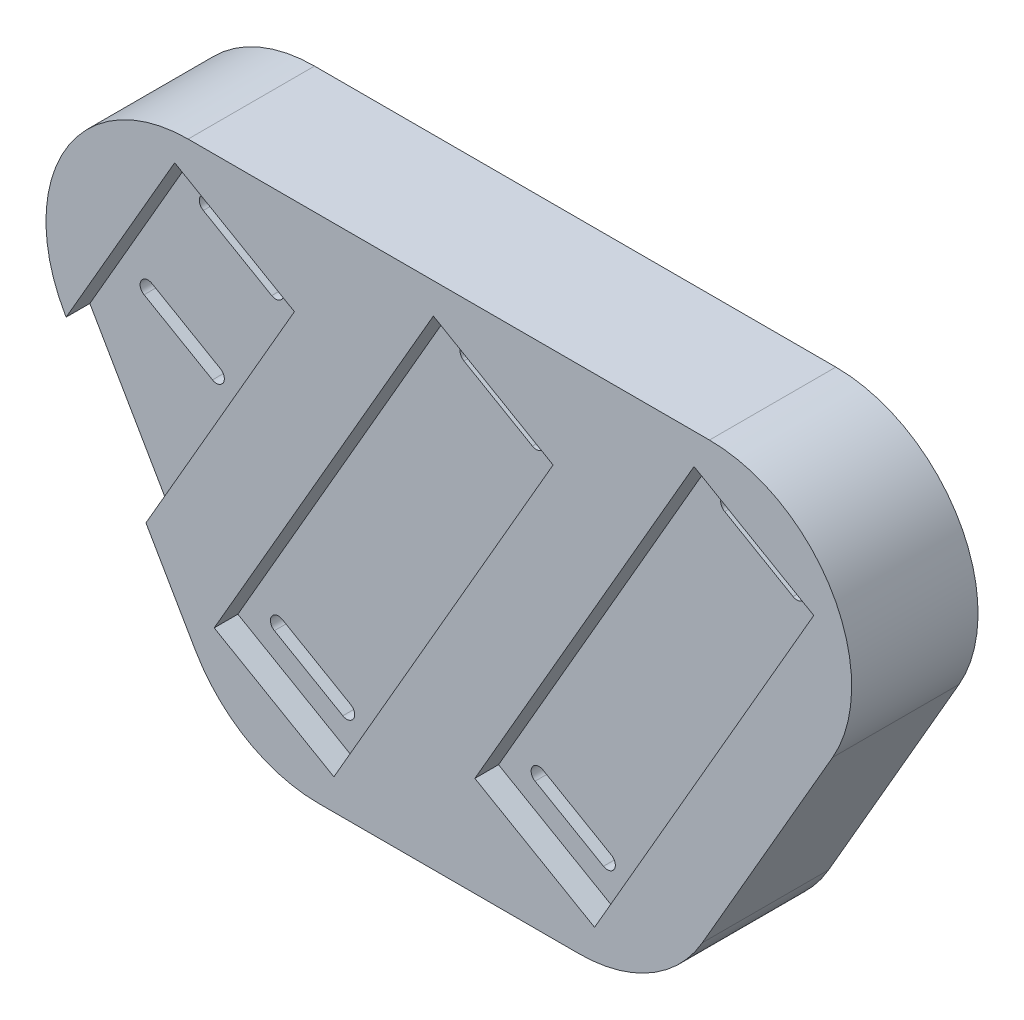
SolidWorks part; units mm, degrees
ref_plane "Front Plane" through (0, 0, 0) normal (0, 0, 1) x (1, 0, 0)
ref_plane "Top Plane" through (0, 0, 0) normal (0, 1, 0) x (1, 0, 0)
ref_plane "Right Plane" through (0, 0, 0) normal (1, 0, 0) x (0, 0, -1)
sketch "Sketch1" plane through (0, 0, 0) normal (0, 0, 1) x (1, 0, 0)
  line L0 (0, 0) -> (-16.5, 0) construction
  line L1 (-8.25, -14.2894) -> (-24.75, -14.2894) construction
  line L2 (0, 0) -> (-8.25, -14.2894) construction
  line L3 (-8.25, -14.2894) -> (-16.5, 0) construction
  line L4 (-16.5, 0) -> (-24.75, -14.2894) construction
  line L5 (-24.75, -14.2894) -> (-33, 0) construction
  line L6 (-33, 0) -> (-16.5, 0) construction
  line L7 (8.9827, 0.5584) -> (-3.9199, -21.7894) construction
  line L8 (-3.9199, -21.7894) -> (-29.0801, -21.7894) construction
  line L9 (-29.0801, -21.7894) -> (-41.9827, 0.5584) construction
  line L10 (-37.9749, 7.5) -> (4.9749, 7.5) construction
  line L11 (7.7942, -4.5) -> (-0.4558, -18.7894)
  line L12 (-8.25, -23.2894) -> (-24.75, -23.2894)
  line L13 (-32.5442, -18.7894) -> (-40.7942, -4.5)
  line L14 (-33, 9) -> (0, 9)
  line L15 (2.5314, -10.6155) -> (3.8304, -11.3655) construction
  line L16 (-16.5, -21.7894) -> (-16.5, -23.2894) construction
  line L17 (-35.5314, -10.6155) -> (-36.8304, -11.3655) construction
  line L18 (-16.5, 7.5) -> (-16.5, 9) construction
  circle A0 centre (-24.75, -14.2894) radius 7.5
  circle A1 centre (-16.5, 0) radius 7.5
  circle A2 centre (0, 0) radius 7.5
  circle A3 centre (0, 0) radius 7.5
  circle A4 centre (-8.25, -14.2894) radius 7.5
  circle A5 centre (-33, 0) radius 7.5
  arc A6 (7.7942, -4.5) -> (0, 9) centre (0, 0) ccw
  arc A7 (-33, 9) -> (-40.7942, -4.5) centre (-33, 0) ccw
  arc A8 (-0.4558, -18.7894) -> (-8.25, -23.2894) centre (-8.25, -14.2894) cw
  arc A9 (-24.75, -23.2894) -> (-32.5442, -18.7894) centre (-24.75, -14.2894) cw
  point P28 (2.5314, -10.6155)
  point P30 (-16.5, -21.7894)
  point P32 (-35.5314, -10.6155)
  point P35 (-16.5, 9)
  dimension "D2" = 15
  dimension "D3" = 16.5
  dimension "D4" = 1.5
  dimension "D5" = 1.5
  dimension "D1" = 0.25
extrude "Boss-Extrude1" add sketch "Sketch1" along normal blind 5
sketch "Sketch2" plane through (0, 0, 5) normal (0, 0, 1) x (1, 0, 0)
  line L0 (-0.4558, -18.7894) -> (7.7942, -4.5) construction
  line L1 (0, 9) -> (-33, 9) construction
  line L2 (-40.7942, -4.5) -> (-32.5442, -18.7894) construction
  line L3 (-24.75, -23.2894) -> (-8.25, -23.2894) construction
  line L4 (-0.4558, -18.7894) -> (7.7942, -4.5)
  line L5 (0, 9) -> (-33, 9)
  line L6 (-40.7942, -4.5) -> (-32.5442, -18.7894)
  line L7 (-24.75, -23.2894) -> (-8.25, -23.2894)
  line L8 (4.0401, 1.9976) -> (-0.2901, 4.4976) construction
  line L9 (3.7901, 1.5646) -> (-0.5401, 4.0646)
  line L10 (4.2901, 2.4306) -> (-0.0401, 4.9306)
  line L11 (-7.9599, -18.787) -> (-12.2901, -16.287) construction
  line L12 (-8.2099, -19.22) -> (-12.5401, -16.72)
  line L13 (-7.7099, -18.354) -> (-12.0401, -15.854)
  line L14 (1.875, 3.2476) -> (-10.125, -17.537) construction
  line L15 (-26.625, -17.537) -> (-24.75, -14.2894) construction
  line L16 (0, 0) -> (1.875, 3.2476) construction
  line L17 (1.875, 3.2476) -> (3.75, 6.4952) construction
  line L18 (-10.125, -17.537) -> (-12, -20.7846) construction
  line L19 (-10.125, -17.537) -> (-8.25, -14.2894) construction
  line L20 (-14.625, 3.2476) -> (-12.75, 6.4952) construction
  line L21 (-14.625, 3.2476) -> (-26.625, -17.537) construction
  line L22 (-16.5, 0) -> (-14.625, 3.2476) construction
  line L23 (-26.625, -17.537) -> (-28.5, -20.7846) construction
  line L24 (-12.4599, 1.9976) -> (-16.7901, 4.4976) construction
  line L25 (-12.7099, 1.5646) -> (-17.0401, 4.0646)
  line L26 (-12.2099, 2.4306) -> (-16.5401, 4.9306)
  line L27 (-24.4599, -18.787) -> (-28.7901, -16.287) construction
  line L28 (-24.7099, -19.22) -> (-29.0401, -16.72)
  line L29 (-24.2099, -18.354) -> (-28.5401, -15.854)
  line L30 (-28.9599, 1.9976) -> (-33.2901, 4.4976) construction
  line L31 (-29.2099, 1.5646) -> (-33.5401, 4.0646)
  line L32 (-28.7099, 2.4306) -> (-33.0401, 4.9306)
  line L33 (-32.7099, -4.4976) -> (-37.0401, -1.9976) construction
  line L34 (-32.9599, -4.9306) -> (-37.2901, -2.4306)
  line L35 (-32.4599, -4.0646) -> (-36.7901, -1.5646)
  line L36 (-31.125, 3.2476) -> (-34.875, -3.2476) construction
  line L37 (-31.125, 3.2476) -> (-29.25, 6.4952) construction
  line L38 (-34.875, -3.2476) -> (-36.75, -6.4952) construction
  line L39 (-31.125, 3.2476) -> (-33, 0) construction
  arc A0 (-8.25, -23.2894) -> (-0.4558, -18.7894) centre (-8.25, -14.2894) ccw construction
  arc A1 (7.7942, -4.5) -> (0, 9) centre (0, 0) ccw construction
  arc A2 (-33, 9) -> (-40.7942, -4.5) centre (-33, 0) ccw construction
  arc A3 (-32.5442, -18.7894) -> (-24.75, -23.2894) centre (-24.75, -14.2894) ccw construction
  arc A4 (-8.25, -23.2894) -> (-0.4558, -18.7894) centre (-8.25, -14.2894) ccw
  arc A5 (7.7942, -4.5) -> (0, 9) centre (0, 0) ccw
  arc A6 (-33, 9) -> (-40.7942, -4.5) centre (-33, 0) ccw
  arc A7 (-32.5442, -18.7894) -> (-24.75, -23.2894) centre (-24.75, -14.2894) ccw
  circle A8 centre (-33, 0) radius 7.5 construction
  circle A9 centre (-24.75, -14.2894) radius 7.5 construction
  circle A10 centre (-16.5, 0) radius 7.5 construction
  circle A11 centre (-8.25, -14.2894) radius 7.5 construction
  circle A12 centre (0, 0) radius 7.5 construction
  circle A13 centre (-33, 0) radius 7.5
  circle A14 centre (-24.75, -14.2894) radius 7.5
  circle A15 centre (-16.5, 0) radius 7.5
  circle A16 centre (-8.25, -14.2894) radius 7.5
  circle A17 centre (0, 0) radius 7.5
  arc A18 (3.7901, 1.5646) -> (4.2901, 2.4306) centre (4.0401, 1.9976) ccw
  arc A19 (-0.0401, 4.9306) -> (-0.5401, 4.0646) centre (-0.2901, 4.4976) ccw
  arc A20 (-8.2099, -19.22) -> (-7.7099, -18.354) centre (-7.9599, -18.787) ccw
  arc A21 (-12.0401, -15.854) -> (-12.5401, -16.72) centre (-12.2901, -16.287) ccw
  arc A22 (-12.7099, 1.5646) -> (-12.2099, 2.4306) centre (-12.4599, 1.9976) ccw
  arc A23 (-16.5401, 4.9306) -> (-17.0401, 4.0646) centre (-16.7901, 4.4976) ccw
  arc A24 (-24.7099, -19.22) -> (-24.2099, -18.354) centre (-24.4599, -18.787) ccw
  arc A25 (-28.5401, -15.854) -> (-29.0401, -16.72) centre (-28.7901, -16.287) ccw
  arc A26 (-29.2099, 1.5646) -> (-28.7099, 2.4306) centre (-28.9599, 1.9976) ccw
  arc A27 (-33.0401, 4.9306) -> (-33.5401, 4.0646) centre (-33.2901, 4.4976) ccw
  arc A28 (-32.9599, -4.9306) -> (-32.4599, -4.0646) centre (-32.7099, -4.4976) ccw
  arc A29 (-36.7901, -1.5646) -> (-37.2901, -2.4306) centre (-37.0401, -1.9976) ccw
  point P8 (-31.125, 3.2476)
  point P25 (1.875, 3.2476)
  point P32 (-10.125, -17.537)
  point P45 (-14.625, 3.2476)
  point P52 (-26.625, -17.537)
  point P64 (-34.875, -3.2476)
  circle M1 centre (-8.25, -14.2894) radius 7.5
  circle M2 centre (0, 0) radius 7.5
  arc M3 (7.7942, -4.5) -> (0, 9) centre (0, 0) ccw
  line M4 (0, 9) -> (-33, 9)
  arc M5 (-33, 9) -> (-40.7942, -4.5) centre (-33, 0) ccw
  line M6 (-40.7942, -4.5) -> (-32.5442, -18.7894)
  arc M7 (-32.5442, -18.7894) -> (-24.75, -23.2894) centre (-24.75, -14.2894) ccw
  line M8 (-24.75, -23.2894) -> (-8.25, -23.2894)
  arc M9 (-8.25, -23.2894) -> (-0.4558, -18.7894) centre (-8.25, -14.2894) ccw
  line M10 (-0.4558, -18.7894) -> (7.7942, -4.5)
  circle M11 centre (-16.5, 0) radius 7.5
  circle M12 centre (-24.75, -14.2894) radius 7.5
  circle M13 centre (-33, 0) radius 7.5
  dimension "D1" = 1
  dimension "D2" = 5
extrude "Boss-Extrude2" add sketch "Sketch2" along normal blind 1.5 contours A21 L13 A20 L12 M1 | M10 M3 M4 M5 M6 M7 M8 M9 M2 M11 M13 M12 M1 | A19 L10 A18 L9 M2 | A23 L26 A22 L25 M11 | A25 L29 A24 L28 M12 | A29 L35 A28 L34 A27 L32 A26 L31 M13
sketch "Sketch3" plane through (0, 0, 6.5) normal (0, 0, 1) x (1, 0, 0)
  line L0 (-40.7942, -4.5) -> (-32.5442, -18.7894) construction
  line L1 (-24.75, -23.2894) -> (-8.25, -23.2894) construction
  line L2 (-0.4558, -18.7894) -> (7.7942, -4.5) construction
  line L3 (0, 9) -> (-33, 9) construction
  line L4 (-40.7942, -4.5) -> (-32.5442, -18.7894)
  line L5 (-24.75, -23.2894) -> (-8.25, -23.2894)
  line L6 (-0.4558, -18.7894) -> (7.7942, -4.5)
  line L7 (0, 9) -> (-33, 9)
  line L8 (6.6014, 2.6839) -> (-7.2736, -21.3483)
  line L9 (6.6014, 2.6839) -> (-0.9764, 7.0589)
  line L10 (-7.2736, -21.3483) -> (-14.8514, -16.9733)
  line L11 (-0.9764, 7.0589) -> (-14.8514, -16.9733)
  line L12 (6.6014, 2.6839) -> (-14.8514, -16.9733) construction
  line L13 (-7.2736, -21.3483) -> (-0.9764, 7.0589) construction
  line L14 (-10.125, -17.537) -> (-12, -20.7846) construction
  line L15 (-10.125, -17.537) -> (-12, -20.7846) construction
  line L16 (-10.375, -17.97) -> (-11.0625, -19.1608) construction
  line L17 (-8.2099, -19.22) -> (-12.5401, -16.72) construction
  line L18 (-12.7231, -16.037) -> (-13.9139, -15.3495) construction
  line L19 (1.875, 3.2476) -> (-10.125, -17.537) construction
  line L20 (1.875, 3.2476) -> (-10.125, -17.537) construction
  line L21 (-26.625, -17.537) -> (-28.5, -20.7846) construction
  line L22 (-14.625, 3.2476) -> (-26.625, -17.537) construction
  line L23 (-26.625, -17.537) -> (-28.5, -20.7846) construction
  line L24 (-14.625, 3.2476) -> (-26.625, -17.537) construction
  line L25 (-9.8986, 2.6839) -> (-23.7736, -21.3483)
  line L26 (-9.8986, 2.6839) -> (-17.4764, 7.0589)
  line L27 (-23.7736, -21.3483) -> (-31.3514, -16.9733)
  line L28 (-17.4764, 7.0589) -> (-31.3514, -16.9733)
  line L29 (-9.8986, 2.6839) -> (-31.3514, -16.9733) construction
  line L30 (-23.7736, -21.3483) -> (-17.4764, 7.0589) construction
  line L31 (-29.2231, -16.037) -> (-30.4139, -15.3495) construction
  line L32 (-26.875, -17.97) -> (-27.5625, -19.1608) construction
  line L33 (-24.7099, -19.22) -> (-29.0401, -16.72) construction
  line L34 (-26.2736, 2.9004) -> (-35.6702, -13.375)
  line L35 (-26.2736, 2.9004) -> (-33.8514, 7.2754)
  line L37 (-33.8514, 7.2754) -> (-40.7221, -4.625)
  line L38 (-26.2736, 2.9004) -> (-39.6518, -6.4788) construction
  line L39 (-35.6702, -13.375) -> (-33.8514, 7.2754) construction
  line L40 (-31.125, 3.2476) -> (-34.875, -3.2476) construction
  line L41 (-30.875, 3.6806) -> (-30.0625, 5.0879) construction
  line L42 (-28.7099, 2.4306) -> (-33.0401, 4.9306) construction
  line L43 (-30.0625, 5.0879) -> (-29.25, 6.4952) construction
  arc A0 (-32.5442, -18.7894) -> (-24.75, -23.2894) centre (-24.75, -14.2894) ccw construction
  arc A1 (-8.25, -23.2894) -> (-0.4558, -18.7894) centre (-8.25, -14.2894) ccw construction
  arc A2 (7.7942, -4.5) -> (0, 9) centre (0, 0) ccw construction
  arc A3 (-33, 9) -> (-40.7942, -4.5) centre (-33, 0) ccw construction
  arc A4 (-32.5442, -18.7894) -> (-24.75, -23.2894) centre (-24.75, -14.2894) ccw
  arc A5 (-8.25, -23.2894) -> (-0.4558, -18.7894) centre (-8.25, -14.2894) ccw
  arc A6 (7.7942, -4.5) -> (0, 9) centre (0, 0) ccw
  arc A7 (-33, 9) -> (-40.7942, -4.5) centre (-33, 0) ccw
  arc A8 (-12.0401, -15.854) -> (-12.5401, -16.72) centre (-12.2901, -16.287) ccw construction
  arc A9 (-28.5401, -15.854) -> (-29.0401, -16.72) centre (-28.7901, -16.287) ccw construction
  point P13 (-4.125, -7.1447)
  point P30 (-11.0625, -19.1608)
  point P33 (-4.125, -7.1447)
  point P35 (-20.625, -7.1447)
  point P49 (-20.625, -7.1447)
  point P50 (-34.7608, -3.0498)
  line M15 (-0.4558, -18.7894) -> (7.7942, -4.5)
  arc M16 (7.7942, -4.5) -> (0, 9) centre (0, 0) ccw
  line M17 (0, 9) -> (-33, 9)
  arc M18 (-33, 9) -> (-40.7942, -4.5) centre (-33, 0) ccw
  line M19 (-40.7942, -4.5) -> (-32.5442, -18.7894)
  arc M20 (-32.5442, -18.7894) -> (-24.75, -23.2894) centre (-24.75, -14.2894) ccw
  line M21 (-24.75, -23.2894) -> (-8.25, -23.2894)
  arc M22 (-8.25, -23.2894) -> (-0.4558, -18.7894) centre (-8.25, -14.2894) ccw
extrude "Boss-Extrude3" add sketch "Sketch3" along normal blind 1.5 contours L37 L35 L34 L4 L28 L26 L25 L27 L11 L9 L8 L10 M20 M21 M22 M15 M16 M17 M18 M19
equation "\"D3@Sketch1\"=\"D2@Sketch1\"+1.5"
equation "\"D1@Sketch2\"=.65+.35"
